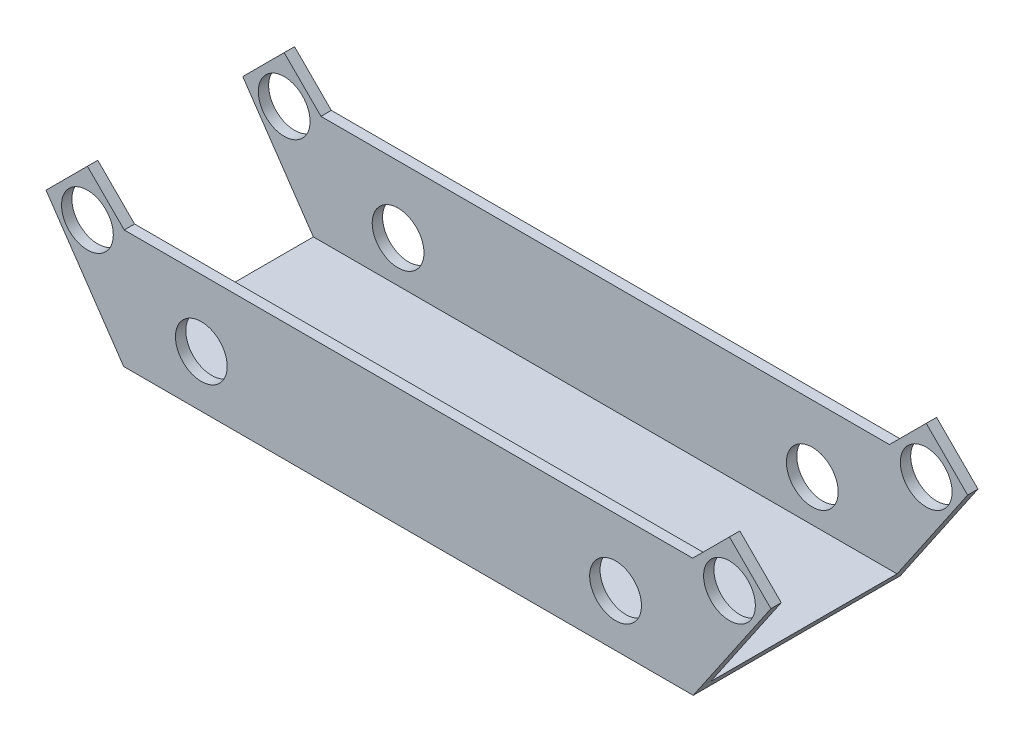
SolidWorks part; units mm, degrees
ref_plane "Front Plane" through (0, 0, 0) normal (0, 0, 1) x (1, 0, 0)
ref_plane "Top Plane" through (0, 0, 0) normal (0, 1, 0) x (1, 0, 0)
ref_plane "Right Plane" through (0, 0, 0) normal (1, 0, 0) x (0, 0, -1)
sketch "Sketch1" plane through (0, 0, 0) normal (0, 1, 0) x (1, 0, 0)
  line L1 (0, 0) -> (140, 0)
  line L2 (0, 0) -> (0, 40)
  line L3 (0, 40) -> (140, 40)
  line L4 (140, 0) -> (140, 40)
  dimension "D1" = 140
  dimension "D2" = 40
extrude "Boss-Extrude1" add sketch "Sketch1" along normal blind 30
sketch "Sketch2" plane through (140, 0, 0) normal (1, 0, 0) x (0, 0, -1)
  line L0 (0, 30) -> (40, 30) construction
  line L1 (2, 2) -> (38, 2)
  line L2 (2, 2) -> (2, 30)
  line L3 (2, 30) -> (38, 30)
  line L4 (38, 2) -> (38, 30)
extrude "Cut-Extrude1" cut sketch "Sketch2" against normal through all
sketch "Sketch3" plane through (0, 0, 0) normal (0, 0, 1) x (1, 0, 0)
  line L0 (0, 0) -> (140, 0) construction
  line L1 (0, 30) -> (0, 0) construction
  line L2 (0, 30) -> (140, 30) construction
  line L3 (15, 0) -> (0, 22)
  line L4 (0, 22) -> (8, 30)
  line L5 (8, 30) -> (15, 19.7333)
  line L6 (15, 19.7333) -> (15, 0)
  line L7 (70, 30) -> (70, 0) construction
  line L8 (125, 19.7333) -> (125, 0)
  line L9 (125, 0) -> (140, 22)
  line L10 (140, 22) -> (132, 30)
  line L11 (132, 30) -> (125, 19.7333)
  line L12 (8, 30) -> (0, 30)
  line L13 (0, 30) -> (0, 22)
  line L14 (0, 0) -> (15, 0)
  line L15 (0, 22) -> (8, 30)
  line L16 (0, 22) -> (0, 0)
  line L17 (15, 0) -> (0, 22)
  line L18 (140, 0) -> (125, 0)
  line L19 (140, 22) -> (140, 0)
  line L20 (125, 0) -> (140, 22)
  line L21 (125, 0) -> (140, 22)
  point P0 (15, 0)
  point P1 (0, 22)
  point P4 (8, 30)
  point P7 (0, 22)
  point P10 (8, 30)
  point P12 (15, 0)
  point P14 (15, 0)
  line M1 (0, 0) -> (140, 0)
  line M2 (140, 0) -> (140, 30)
  line M4 (0, 30) -> (0, 0)
extrude "Cut-Extrude2" cut sketch "Sketch3" against normal through all contours L3 M1 M4 | L9 M1 M2
sketch "Sketch5" plane through (0, 0, 0) normal (0, 0, 1) x (1, 0, 0)
  line L0 (0, 30) -> (140, 30) construction
  line L1 (0, 22) -> (0, 30)
  line L2 (0, 30) -> (8, 30)
  line L3 (8, 30) -> (0, 22)
  line L4 (70, 30) -> (70, 0)
  line L5 (15, 0) -> (125, 0) construction
  line L6 (140, 22) -> (140, 30)
  line L7 (140, 30) -> (132, 30)
  line L8 (132, 30) -> (140, 22)
  point P0 (8, 30)
  line M5 (0, 30) -> (0, 22)
  line M9 (140, 22) -> (140, 30)
  line M10 (140, 30) -> (0, 30)
extrude "Cut-Extrude3" cut sketch "Sketch5" against normal through all contours L3 M10 M5 | L8 M10 M9
sketch "Sketch6" plane through (0, 0, 0) normal (0, 0, 1) x (1, 0, 0)
  line L0 (15, 0) -> (0, 22)
  line L1 (0, 22) -> (8, 30)
  line L2 (8, 30) -> (15.1073, 22.8927)
  line L4 (70, 30) -> (70, 0) construction
  line L5 (8, 30) -> (132, 30) construction
  line L6 (15, 0) -> (125, 0) construction
  line L7 (132, 30) -> (124.8927, 22.8927)
  line L8 (15.1073, 22.8927) -> (124.8927, 22.8927)
  line L9 (132, 30) -> (8, 30)
  circle A0 centre (8, 21) radius 5
  circle A1 centre (132, 21) radius 5
  circle A2 centre (30, 10) radius 5
  circle A3 centre (110, 10) radius 5
  line M6 (132, 30) -> (8, 30)
  dimension "D1" = 10
  dimension "D2" = 40
extrude "Cut-Extrude6" cut sketch "Sketch6" against normal through all contours L4 L9 L2 L8 | L4 L8 L7 M6 | A1 | A3 | A2 | A0
